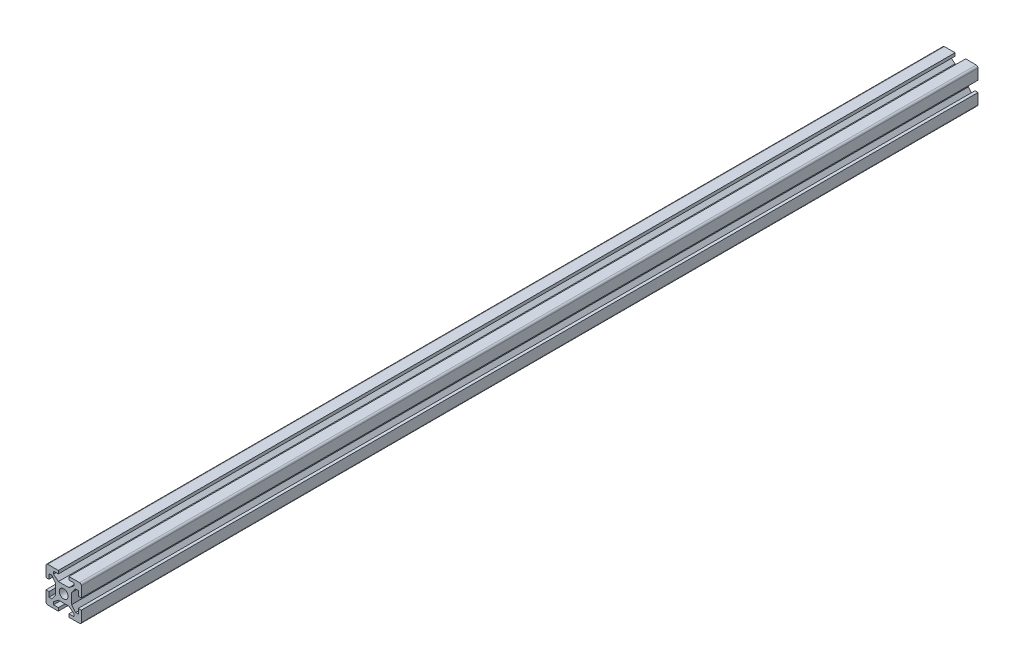
SolidWorks part; units mm, degrees
material "6063-T5"
ref_plane "Front Plane" through (0, 0, 0) normal (0, 0, 1) x (1, 0, 0)
ref_plane "Top Plane" through (0, 0, 0) normal (0, 1, 0) x (1, 0, 0)
ref_plane "Right Plane" through (0, 0, 0) normal (1, 0, 0) x (0, 0, -1)
sketch "Sketch1" plane through (0, 0, 0) normal (0, 0, 1) x (1, 0, 0)
  line L18 (0, 0) -> (0, 20.5117) construction
  line L39 (-10, 10) -> (-3, 10)
  line L41 (10, 10) -> (3, 10)
  line L43 (-10, 10) -> (-10, 3)
  line L45 (-10, -10) -> (-10, -3)
  line L47 (-10, -10) -> (-3, -10)
  line L49 (3, -10) -> (10, -10)
  line L51 (10, -10) -> (10, -3)
  line L53 (10, 3) -> (10, 10)
  line L55 (-3, 10) -> (-3, 8.2726)
  line L56 (-3, 8.2726) -> (-5.7838, 8.2726)
  line L57 (-5.7838, 8.2726) -> (-5.7838, 6.748)
  line L58 (-5.7838, 6.748) -> (-3, 4.5508)
  line L59 (-3, 4.5508) -> (3, 4.5508)
  line L60 (3, 10) -> (3, 8.2726)
  line L61 (3, 8.2726) -> (5.7838, 8.2726)
  line L62 (5.7838, 8.2726) -> (5.7838, 6.748)
  line L63 (5.7838, 6.748) -> (3, 4.5508)
  line L64 (10, 3) -> (8.2726, 3)
  line L65 (8.2726, 3) -> (8.2726, 5.7838)
  line L66 (8.2726, 5.7838) -> (6.748, 5.7838)
  line L67 (10, -3) -> (8.2726, -3)
  line L68 (8.2726, -3) -> (8.2726, -5.7838)
  line L69 (8.2726, -5.7838) -> (6.748, -5.7838)
  line L70 (4.55, -2.9994) -> (4.55, 3.0006)
  line L71 (4.55, -2.9994) -> (6.748, -5.7838)
  line L72 (4.55, 3.0006) -> (6.748, 5.7838)
  line L73 (3, -10) -> (3, -8.2726)
  line L74 (3, -8.2726) -> (5.7838, -8.2726)
  line L75 (5.7838, -8.2726) -> (5.7838, -6.748)
  line L76 (-3, -10) -> (-3, -8.2726)
  line L77 (-3, -8.2726) -> (-5.7838, -8.2726)
  line L78 (-5.7838, -8.2726) -> (-5.7838, -6.748)
  line L79 (2.9994, -4.55) -> (-3.0006, -4.55)
  line L80 (5.7838, -6.748) -> (2.9994, -4.55)
  line L81 (-5.7838, -6.748) -> (-3.0006, -4.55)
  line L82 (-10, -3) -> (-8.2726, -3)
  line L83 (-8.2726, -3) -> (-8.2726, -5.7838)
  line L84 (-8.2726, -5.7838) -> (-6.748, -5.7838)
  line L85 (-10, 3) -> (-8.2726, 3)
  line L86 (-8.2726, 3) -> (-8.2726, 5.7838)
  line L87 (-8.2726, 5.7838) -> (-6.748, 5.7838)
  line L88 (-4.55, -3.0006) -> (-4.55, 2.9994)
  line L89 (-6.748, -5.7838) -> (-4.55, -3.0006)
  line L90 (-4.55, 2.9994) -> (-6.748, 5.7838)
  dimension "D9" = 7
  dimension "D17" = 2.7838
  dimension "D1" = 20
  dimension "D2" = 20
  dimension "D3" = 10
  dimension "D4" = 10
  dimension "D5" = 7
  dimension "D6" = 7
  dimension "D7" = 7
  dimension "D8" = 7
  dimension "D10" = 7
  dimension "D11" = 7
  dimension "D12" = 7
  dimension "D13" = 6
  dimension "D14" = 3
  dimension "D15" = 3.5464
  dimension "D16" = 1.5246
  dimension "D18" = 1.7274
  dimension "D19" = 4.55
  dimension "D20" = 4.55
  dimension "D21" = 4.55
  dimension "D22" = 10
  dimension "D23" = 10
  dimension "D24" = 10
  dimension "D25" = 10
  dimension "D26" = 10
  dimension "D27" = 10
  dimension "D28" = 6
  dimension "D29" = 6
  dimension "D30" = 6
  dimension "D31" = 6
extrude "Boss-Extrude1" add sketch "Sketch1" along normal mid plane 508
sketch "Sketch2" plane through (0, 0, 254) normal (0, 0, 1) x (1, 0, 0)
  circle A0 centre (0, 0) radius 2.5
  dimension "D1" = 5
extrude "Cut-Extrude1" cut sketch "Sketch2" against normal through all both and the other way through all
fillet "Fillet1" radius 1 1 edges at (10, 10, 0)
fillet "Fillet2" radius 1 3 edges at (-10, -10, 0) (10, -10, 0) (-10, 10, 0)
